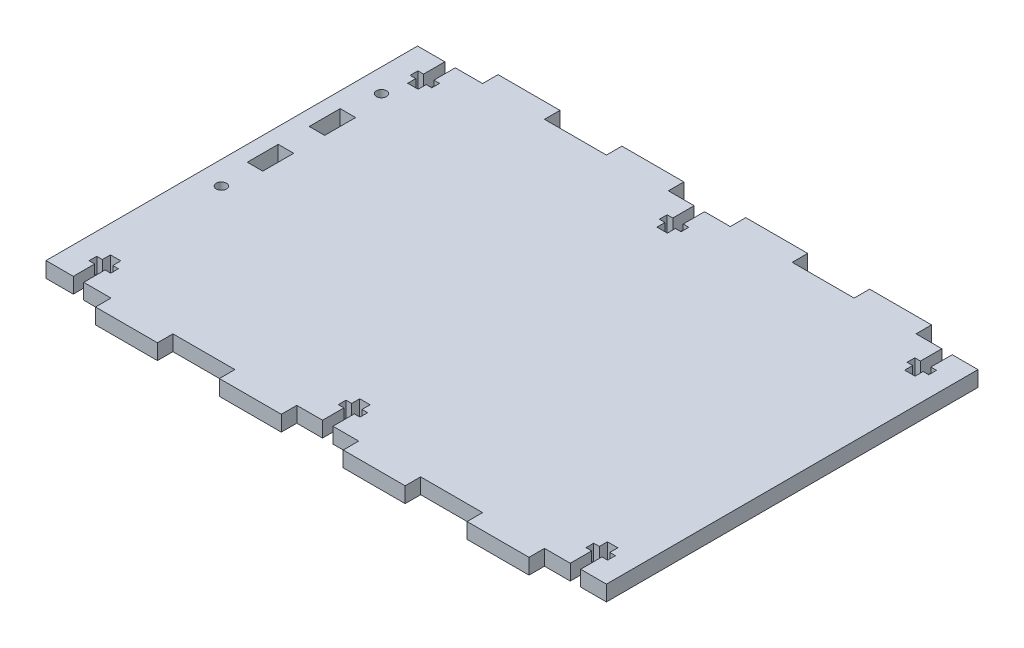
SolidWorks part; units mm, degrees
ref_plane "Front Plane" through (0, 0, 0) normal (0, 0, 1) x (1, 0, 0)
ref_plane "Top Plane" through (0, 0, 0) normal (0, 1, 0) x (1, 0, 0)
ref_plane "Right Plane" through (0, 0, 0) normal (1, 0, 0) x (0, 0, -1)
sketch "Sketch1" plane through (0, 0, 0) normal (0, 0, 1) x (1, 0, 0)
  line L0 (90.51, -15.875) -> (90.51, 155.575) construction
  line L1 (-139.3499, 155.575) -> (90.51, 155.575)
  line L2 (-139.3499, 155.575) -> (-139.3499, 149.225)
  line L3 (-139.3499, 149.225) -> (90.51, 149.225)
  line L4 (90.51, 155.575) -> (90.51, 149.225)
  dimension "D1" = 6.35
extrude "Boss-Extrude1" add sketch "Sketch1" along normal blind 152.4
sketch "Sketch2" plane through (0, 155.575, 0) normal (0, 1, 0) x (1, 0, 0)
  line L0 (65.11, 0) -> (65.11, 6.35)
  line L1 (90.51, 0) -> (-139.3499, 0) construction
  line L2 (-139.3499, 6.35) -> (-112.69, 6.35) construction
  line L3 (65.11, 6.35) -> (39.71, 6.35)
  line L4 (39.71, 6.35) -> (39.71, 0)
  line L5 (90.51, 0) -> (65.11, 0)
  line L6 (65.11, 0) -> (39.71, 0)
  line L9 (90.51, 0) -> (-139.3499, 0)
  line L10 (-139.3499, 0) -> (-139.3499, -152.4)
  line L11 (-139.3499, -152.4) -> (90.51, -152.4)
  line L12 (90.51, -152.4) -> (90.51, 0)
  line L13 (39.71, 0) -> (-139.3499, 0)
  line L14 (-139.3499, 0) -> (-139.3499, -152.4)
  line L15 (-139.3499, -152.4) -> (90.51, -152.4)
  line L16 (90.51, -152.4) -> (90.51, 0)
  line M7 (90.51, 0) -> (-139.3499, 0)
  dimension "D1" = 25.4
  dimension "D2" = 25.4
  dimension "D3" = 0
extrude "Boss-Extrude2" add sketch "Sketch2" against normal blind 6.35 contours L3 L4 L0 M7
pattern_linear "LPattern1" count 4 spacing 50.8 along (-1, 0, 0) of "Boss-Extrude2"
sketch "Sketch3" plane through (0, 0, 152.4) normal (0, 0, 1) x (1, 0, 0)
  line L0 (90.51, 155.575) -> (-139.3499, 155.575) construction
  line L1 (65.11, 155.575) -> (39.71, 155.575)
  line L2 (65.11, 155.575) -> (65.11, 149.225)
  line L3 (65.11, 149.225) -> (39.71, 149.225)
  line L4 (39.71, 155.575) -> (39.71, 149.225)
  line L5 (-139.3499, 149.225) -> (90.51, 149.225) construction
  dimension "D1" = 25.4
  dimension "D2" = 25.4
extrude "Boss-Extrude3" add sketch "Sketch3" along normal blind 6.35
pattern_linear "LPattern2" count 4 spacing 50.8 along (-1, 0, 0) of "Boss-Extrude3"
sketch "Sketch4" plane through (0, 155.575, 0) normal (0, 1, 0) x (1, 0, 0)
  line L0 (-139.3499, 0) -> (-112.69, 0) construction
  line L1 (65.11, 0) -> (90.51, 0) construction
  line L2 (-126.0199, 0) -> (-126.0199, -13.6148) construction
  line L3 (-112.69, 0) -> (-139.3499, 0) construction
  line L4 (-23.79, 0) -> (-23.79, -16.5479) construction
  line L5 (-11.09, 0) -> (-36.49, 0) construction
  line L6 (77.81, 0) -> (77.81, -21.5198) construction
  line L7 (90.51, 0) -> (65.11, 0) construction
  line L8 (77.81, -152.4) -> (77.81, -137.4626) construction
  line L9 (90.51, -152.4) -> (65.11, -152.4) construction
  line L10 (-23.79, -152.4) -> (-23.79, -137.4626) construction
  line L11 (-11.09, -152.4) -> (-36.49, -152.4) construction
  line L12 (-126.0199, -152.4) -> (-126.0199, -137.4626) construction
  line L13 (-112.69, -152.4) -> (-139.3499, -152.4) construction
  line L14 (-139.3499, -152.4) -> (-112.69, -152.4) construction
  line L15 (-36.49, -152.4) -> (-11.09, -152.4) construction
  line B0 (-123.8863, 0) -> (-128.1535, 0)
  line B1 (-128.1535, -11.938) -> (-130.4649, -11.938)
  line B2 (-130.4649, -11.938) -> (-130.4649, -8.763)
  line B3 (-130.4649, -8.763) -> (-128.1535, -8.763)
  line B4 (-128.1535, -8.763) -> (-128.1535, 0)
  line B5 (-128.1535, -11.938) -> (-128.1535, -15.24)
  line B6 (-128.1535, -15.24) -> (-123.8863, -15.24)
  line B7 (-123.8863, -11.938) -> (-123.8863, -15.24)
  line B8 (-123.8863, -8.763) -> (-123.8863, 0)
  line B9 (-121.5749, -8.763) -> (-123.8863, -8.763)
  line B10 (-121.5749, -11.938) -> (-121.5749, -8.763)
  line B11 (-123.8863, -11.938) -> (-121.5749, -11.938)
  line B12 (-21.6564, 0) -> (-25.9236, 0)
  line B13 (-25.9236, -11.938) -> (-28.235, -11.938)
  line B14 (-28.235, -11.938) -> (-28.235, -8.763)
  line B15 (-28.235, -8.763) -> (-25.9236, -8.763)
  line B16 (-25.9236, -8.763) -> (-25.9236, 0)
  line B17 (-25.9236, -11.938) -> (-25.9236, -15.24)
  line B18 (-25.9236, -15.24) -> (-21.6564, -15.24)
  line B19 (-21.6564, -11.938) -> (-21.6564, -15.24)
  line B20 (-21.6564, -8.763) -> (-21.6564, 0)
  line B21 (-19.345, -8.763) -> (-21.6564, -8.763)
  line B22 (-19.345, -11.938) -> (-19.345, -8.763)
  line B23 (-21.6564, -11.938) -> (-19.345, -11.938)
  line B24 (79.9436, 0) -> (75.6764, 0)
  line B25 (75.6764, -11.938) -> (73.365, -11.938)
  line B26 (73.365, -11.938) -> (73.365, -8.763)
  line B27 (73.365, -8.763) -> (75.6764, -8.763)
  line B28 (75.6764, -8.763) -> (75.6764, 0)
  line B29 (75.6764, -11.938) -> (75.6764, -15.24)
  line B30 (75.6764, -15.24) -> (79.9436, -15.24)
  line B31 (79.9436, -11.938) -> (79.9436, -15.24)
  line B32 (79.9436, -8.763) -> (79.9436, 0)
  line B33 (82.255, -8.763) -> (79.9436, -8.763)
  line B34 (82.255, -11.938) -> (82.255, -8.763)
  line B35 (79.9436, -11.938) -> (82.255, -11.938)
  line B36 (-128.1535, -152.4) -> (-123.8863, -152.4)
  line B37 (-123.8863, -140.462) -> (-121.5749, -140.462)
  line B38 (-121.5749, -140.462) -> (-121.5749, -143.637)
  line B39 (-121.5749, -143.637) -> (-123.8863, -143.637)
  line B40 (-123.8863, -143.637) -> (-123.8863, -152.4)
  line B41 (-123.8863, -140.462) -> (-123.8863, -137.16)
  line B42 (-123.8863, -137.16) -> (-128.1535, -137.16)
  line B43 (-128.1535, -140.462) -> (-128.1535, -137.16)
  line B44 (-128.1535, -143.637) -> (-128.1535, -152.4)
  line B45 (-130.4649, -143.637) -> (-128.1535, -143.637)
  line B46 (-130.4649, -140.462) -> (-130.4649, -143.637)
  line B47 (-128.1535, -140.462) -> (-130.4649, -140.462)
  line B48 (-25.9236, -152.4) -> (-21.6564, -152.4)
  line B49 (-21.6564, -140.462) -> (-19.345, -140.462)
  line B50 (-19.345, -140.462) -> (-19.345, -143.637)
  line B51 (-19.345, -143.637) -> (-21.6564, -143.637)
  line B52 (-21.6564, -143.637) -> (-21.6564, -152.4)
  line B53 (-21.6564, -140.462) -> (-21.6564, -137.16)
  line B54 (-21.6564, -137.16) -> (-25.9236, -137.16)
  line B55 (-25.9236, -140.462) -> (-25.9236, -137.16)
  line B56 (-25.9236, -143.637) -> (-25.9236, -152.4)
  line B57 (-28.235, -143.637) -> (-25.9236, -143.637)
  line B58 (-28.235, -140.462) -> (-28.235, -143.637)
  line B59 (-25.9236, -140.462) -> (-28.235, -140.462)
  line B60 (75.6764, -152.4) -> (79.9436, -152.4)
  line B61 (79.9436, -140.462) -> (82.255, -140.462)
  line B62 (82.255, -140.462) -> (82.255, -143.637)
  line B63 (82.255, -143.637) -> (79.9436, -143.637)
  line B64 (79.9436, -143.637) -> (79.9436, -152.4)
  line B65 (79.9436, -140.462) -> (79.9436, -137.16)
  line B66 (79.9436, -137.16) -> (75.6764, -137.16)
  line B67 (75.6764, -140.462) -> (75.6764, -137.16)
  line B68 (75.6764, -143.637) -> (75.6764, -152.4)
  line B69 (73.365, -143.637) -> (75.6764, -143.637)
  line B70 (73.365, -140.462) -> (73.365, -143.637)
  line B71 (75.6764, -140.462) -> (73.365, -140.462)
sketch_block_instance "TSlot-1"
sketch_block "TSlot" parameters "D1"=3.302, "D2"=3.175
sketch_block_instance "TSlot-3"
sketch_block_instance "TSlot-4"
sketch_block_instance "TSlot-9"
sketch_block_instance "TSlot-11"
sketch_block_instance "TSlot-12"
extrude "Cut-Extrude1" cut sketch "Sketch4" against normal blind 6.35
sketch "Sketch5" plane through (0, 155.575, 0) normal (0, 1, 0) x (1, 0, 0)
  line L0 (-132.9999, -55.2358) -> (-132.9999, -140.7347) construction
  line L1 (-132.9999, -38.1) -> (-126.6499, -38.1)
  line L2 (-132.9999, -38.1) -> (-132.9999, -50.8)
  line L3 (-132.9999, -50.8) -> (-126.6499, -50.8)
  line L4 (-126.6499, -38.1) -> (-126.6499, -50.8)
  line L5 (-132.9999, -63.5) -> (-126.6499, -63.5)
  line L6 (-132.9999, -63.5) -> (-132.9999, -76.2)
  line L7 (-132.9999, -76.2) -> (-126.6499, -76.2)
  line L8 (-126.6499, -63.5) -> (-126.6499, -76.2)
  line L10 (-139.3499, -152.4) -> (-139.3499, 0) construction
  line L11 (-128.1535, 0) -> (-139.3499, 0) construction
  dimension "D1" = 12.7
  dimension "D2" = 6.35
  dimension "D3" = 6.35
  dimension "D4" = 12.7
  dimension "D5" = 12.7
  dimension "D6" = 6.35
  dimension "D7" = 38.1
extrude "Cut-Extrude2" cut sketch "Sketch5" against normal through all
sketch "Sketch6" plane through (0, 155.575, 0) normal (0, 1, 0) x (1, 0, 0)
  line L0 (-132.9999, -22.1864) -> (-126.6499, -26.4536) construction
  line L1 (-132.9999, -26.4536) -> (-126.6499, -22.1864) construction
  line L2 (-132.9999, -87.8464) -> (-126.6499, -92.1136) construction
  line L3 (-132.9999, -92.1136) -> (-126.6499, -87.8464) construction
  circle A0 centre (-129.8249, -89.98) radius 2.0955
  circle A1 centre (-129.8249, -24.32) radius 2.0955
  dimension "D1" = 4.191
extrude "Cut-Extrude3" cut sketch "Sketch6" against normal through all
